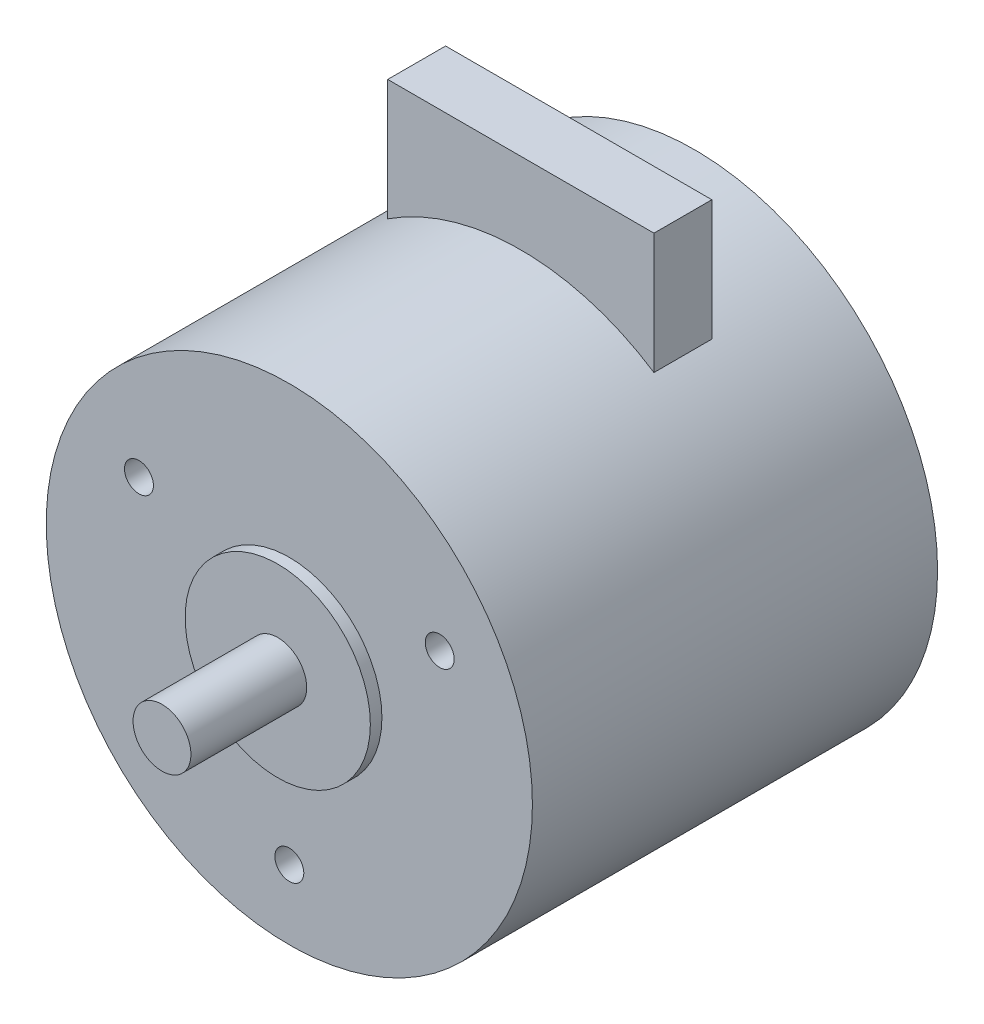
SolidWorks part; units mm, degrees
ref_plane "Front Plane" through (0, 0, 0) normal (0, 0, 1) x (1, 0, 0)
ref_plane "Top Plane" through (0, 0, 0) normal (0, 1, 0) x (1, 0, 0)
ref_plane "Right Plane" through (0, 0, 0) normal (1, 0, 0) x (0, 0, -1)
sketch "Sketch1" plane through (0, 0, 0) normal (0, 0, 1) x (1, 0, 0)
  circle A0 centre (0, 0) radius 21
  dimension "D1" = 42
extrude "Boss-Extrude1" add sketch "Sketch1" along normal blind 35
sketch "Sketch2" plane through (0, 0, 35) normal (0, 0, 1) x (1, 0, 0)
  circle A0 centre (0, 0) radius 8
extrude "Boss-Extrude2" add sketch "Sketch2" along normal blind 1
sketch "Sketch3" plane through (0, 0, 36) normal (0, 0, 1) x (1, 0, 0)
  circle A0 centre (0, 0) radius 2.5
extrude "Boss-Extrude3" add sketch "Sketch3" along normal blind 10
sketch "Sketch4" plane through (0, 0, 0) normal (0, 0, -1) x (-1, 0, 0)
  line L1 (-11.5, 28) -> (11.5, 28)
  line L2 (-11.5, 28) -> (-11.5, 13.8606)
  line L3 (-11.5, 13.8606) -> (11.5, 13.8606)
  line L4 (11.5, 28) -> (11.5, 13.8606)
  point P5 (0, 28)
  dimension "D1" = 28
  dimension "D2" = 23
extrude "Boss-Extrude4" add sketch "Sketch4" against normal blind 5 from offset 10 offset against normal yes
sketch "Sketch6" plane through (0, 0, 35) normal (0, 0, 1) x (1, 0, 0)
  circle A0 centre (0, -15) radius 1.25
  circle A1 centre (-12.9904, 7.5) radius 1.25
  circle A2 centre (12.9904, 7.5) radius 1.25
  dimension "D1" = 2.5
  dimension "D2" = 15
  dimension "D3" = 3
extrude "Cut-Extrude1" cut sketch "Sketch6" against normal blind 5
